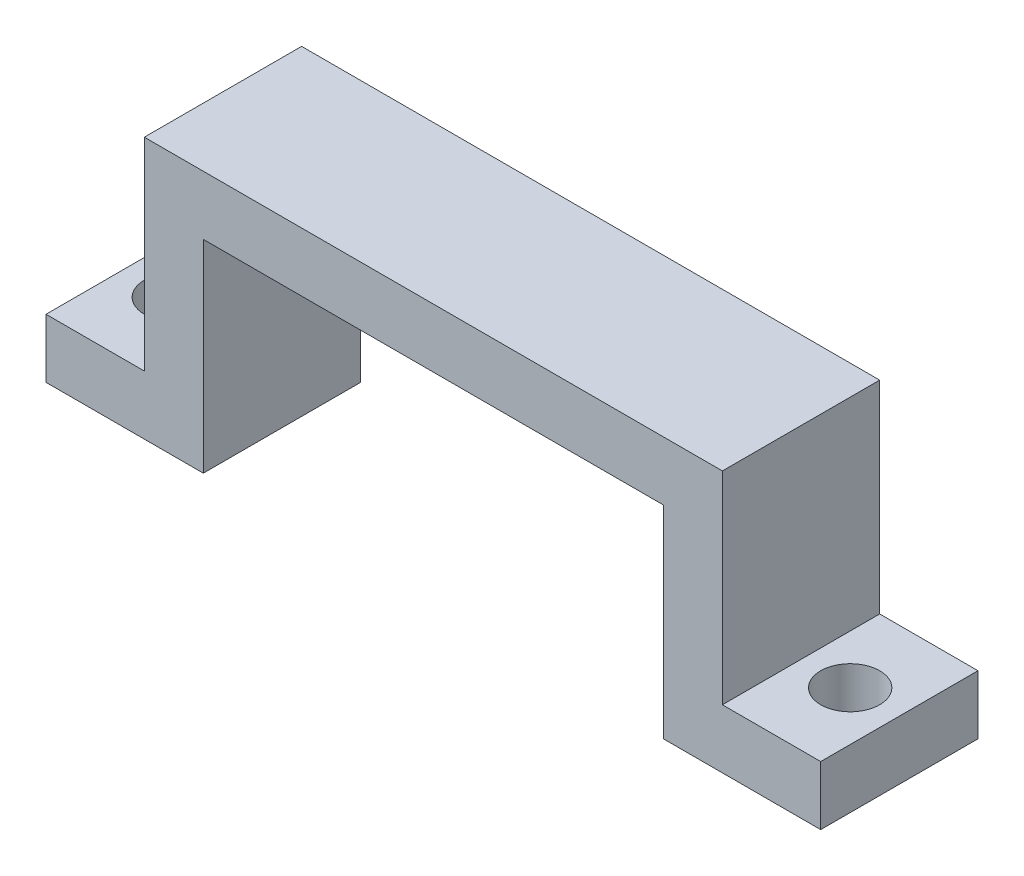
SolidWorks part; units mm, degrees
ref_plane "Front Plane" through (0, 0, 0) normal (0, 0, 1) x (1, 0, 0)
ref_plane "Top Plane" through (0, 0, 0) normal (0, 1, 0) x (1, 0, 0)
ref_plane "Right Plane" through (0, 0, 0) normal (1, 0, 0) x (0, 0, -1)
sketch "Sketch1" plane through (0, 0, 0) normal (0, 1, 0) x (1, 0, 0)
  line L1 (-14.7, 4) -> (14.7, 4)
  line L2 (-14.7, 4) -> (-14.7, -4)
  line L3 (-14.7, -4) -> (14.7, -4)
  line L4 (14.7, 4) -> (14.7, -4)
  line L5 (-14.7, 4) -> (14.7, -4) construction
  line L6 (-14.7, -4) -> (14.7, 4) construction
  point P0 (0, 0)
  dimension "D1" = 29.4
  dimension "D2" = 8
extrude "Boss-Extrude1" add sketch "Sketch1" against normal blind 13.3
sketch "Sketch4" plane through (0, 0, 4) normal (0, 0, 1) x (1, 0, 0)
  line L0 (-14.7, -13.3) -> (14.7, -13.3) construction
  line L1 (-11.7, -13.3) -> (11.7, -13.3)
  line L2 (-11.7, -13.3) -> (-11.7, -3)
  line L3 (-11.7, -3) -> (11.7, -3)
  line L4 (11.7, -13.3) -> (11.7, -3)
  line L5 (-14.7, -13.3) -> (-14.7, 0) construction
  line L6 (-14.7, 0) -> (14.7, 0) construction
  line L7 (14.7, -13.3) -> (14.7, 0) construction
  dimension "D1" = 3
  dimension "D2" = 3
  dimension "D3" = 3
extrude "Cut-Extrude2" cut sketch "Sketch4" against normal up to next
sketch "Sketch5" plane through (14.7, 0, 0) normal (1, 0, 0) x (0, 0, -1)
  line L0 (4, -13.3) -> (4, 0) construction
  line L1 (-4, -13.3) -> (4, -13.3)
  line L2 (-4, -13.3) -> (-4, -10.3)
  line L3 (-4, -10.3) -> (4, -10.3)
  line L4 (4, -13.3) -> (4, -10.3)
  dimension "D1" = 3
extrude "Boss-Extrude3" add sketch "Sketch5" along normal blind 5
sketch "Sketch6" plane through (0, -10.3, 0) normal (0, 1, 0) x (1, 0, 0)
  circle A1 centre (17.2, 0) radius 1.5
  dimension "D1" = 3
extrude "Cut-Extrude3" cut sketch "Sketch6" against normal up to next
mirror "Mirror2" about plane through (0, 0, 0) normal (1, 0, 0) of "Boss-Extrude3", "Cut-Extrude3"
